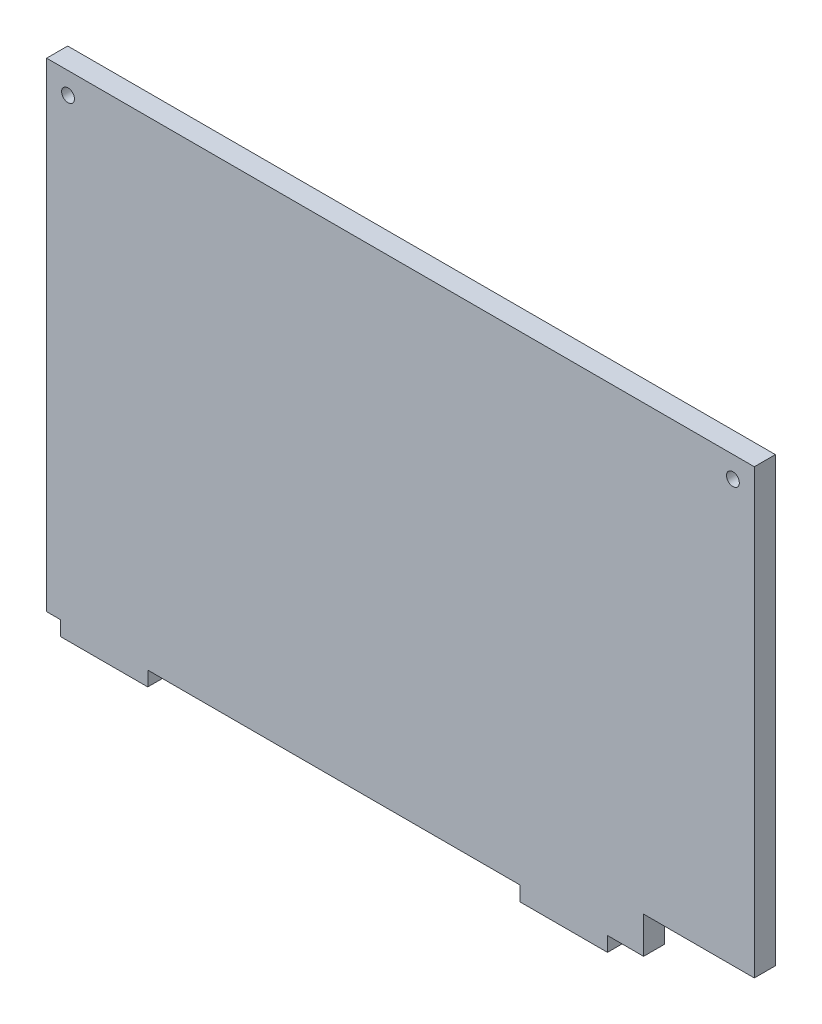
SolidWorks part; units mm, degrees
material "Acrylic (Medium-high impact)"
ref_plane "Front Plane" through (0, 0, 0) normal (0, 0, 1) x (1, 0, 0)
ref_plane "Top Plane" through (0, 0, 0) normal (0, 1, 0) x (1, 0, 0)
ref_plane "Right Plane" through (0, 0, 0) normal (1, 0, 0) x (0, 0, -1)
sketch "Sketch1" plane through (0, 0, 0) normal (0, 0, 1) x (1, 0, 0)
  line L0 (0, 0) -> (10.125, 0)
  line L1 (10.125, 0) -> (10.125, -4.1)
  line L2 (10.125, -4.1) -> (34.625, -4.1)
  line L3 (34.625, -4.1) -> (34.625, 0)
  line L4 (34.625, 0) -> (138.875, 0)
  line L5 (138.875, 0) -> (138.875, -4.1)
  line L6 (138.875, -4.1) -> (163.375, -4.1)
  line L7 (163.375, -4.1) -> (163.375, 0)
  line L8 (163.375, 0) -> (173.5, 0)
  line L9 (173.5, 0) -> (173.5, 10.25)
  line L10 (173.5, 10.25) -> (204.5, 10.25)
  line L11 (0, 0) -> (0, 134.25)
  line L12 (0, 134.25) -> (204.5, 134.25)
  line L13 (204.5, 134.25) -> (204.5, 10.25)
  dimension "D1" = 24.5
  dimension "D2" = 24.5
  dimension "D3" = 173.5
  dimension "D4" = 10.125
  dimension "D5" = 10.125
  dimension "D6" = 4.1
  dimension "D7" = 4.1
  dimension "D8" = 31
  dimension "D9" = 10.25
  dimension "D10" = 124
extrude "Boss-Extrude1" add sketch "Sketch1" along normal blind 5.9
other "Move Face1" face at (0, 67.125, 2.95) parameters "D1"=6.3
hole_wizard "CSK for M3 Flat Head Machine Screw1" positions "Sketch2" profile "Sketch3" countersink size "M3" standard "ANSI Metric"
sketch "Sketch2" plane through (0, 0, 5.9) normal (0, 0, 1) x (1, 0, 0)
  point P0 (12.3, 128.25)
  point P3 (198.5, 128.25)
sketch "Sketch3" plane through (12.3, 128.25, 5.9) normal (1, 0, 0) x (0, -1, 0)
  line L0 (0, 0) -> (0, 11.0215)
  line L1 (0, 11.0215) -> (1.7, 10)
  line L2 (1.7, 10) -> (1.7, 1.45)
  line L3 (1.7, 1.45) -> (3.15, 0)
  line L5 (3.15, 0) -> (0, 0)
  line L6 (-1.7, 1.45) -> (-3.15, 0) construction
  line L10 (0, 11.0215) -> (-1.7, 10) construction
  line L11 (0, -6.35) -> (0, 107.95) construction
  dimension "Hole Dia." = 3.4
  dimension "Hole Depth" = 10
  dimension "Near C'Sink Dia." = 6.3
  dimension "Near C'Sink Angle" = 90
  dimension "Drill Angle" = 118
hole_wizard "CSK for #4 Flat Head Machine Screw (100)1" positions "Sketch4" profile "Sketch5" countersink size "#4" standard "ANSI Inch"
sketch "Sketch4" plane through (0, 0, 0) normal (0, 0, 1) x (1, 0, 0)
  point P0 (196.4, 15.25)
  point P3 (14.4, 15.25)
sketch "Sketch5" plane through (196.4, 15.25, 0) normal (1, 0, 0) x (0, 1, 0)
  line L0 (0, 0) -> (0, 10.9806)
  line L1 (0, 10.9806) -> (1.6319, 10)
  line L2 (1.6319, 10) -> (1.6319, 1.0284)
  line L3 (1.6319, 1.0284) -> (2.8575, 0)
  line L5 (2.8575, 0) -> (0, 0)
  line L6 (-1.6319, 1.0284) -> (-2.8575, 0) construction
  line L10 (0, 10.9806) -> (-1.632, 10) construction
  line L11 (0, -6.35) -> (0, 107.95) construction
  dimension "Hole Dia." = 3.2639
  dimension "Hole Depth" = 10
  dimension "Near C'Sink Dia." = 5.715
  dimension "Near C'Sink Angle" = 100
  dimension "Drill Angle" = 118
hole_wizard "CSK for M3 Flat Head Machine Screw2" positions "Sketch6" profile "Sketch7" countersink size "M3" standard "ANSI Metric" end condition through all
sketch "Sketch6" plane through (0, 0, 0) normal (0, 0, -1) x (-1, 0, 0)
  point P0 (-198.5, 128.25)
  point P3 (-12.3, 128.25)
sketch "Sketch7" plane through (198.5, 128.25, 0) normal (1, 0, 0) x (0, 1, 0)
  line L0 (0, 0) -> (0, 5.9)
  line L1 (0, 5.9) -> (1.8, 5.9)
  line L2 (1.8, 5.9) -> (1.8, 1.35)
  line L3 (1.8, 1.35) -> (3.15, 0)
  line L5 (3.15, 0) -> (0, 0)
  line L6 (-1.8, 1.35) -> (-3.15, 0) construction
  line L11 (0, -6.35) -> (0, 107.95) construction
  dimension "Thru Hole Dia." = 3.6
  dimension "Thru Hole Depth" = 5.9
  dimension "Near C'Sink Dia." = 6.3
  dimension "Near C'Sink Angle" = 90
